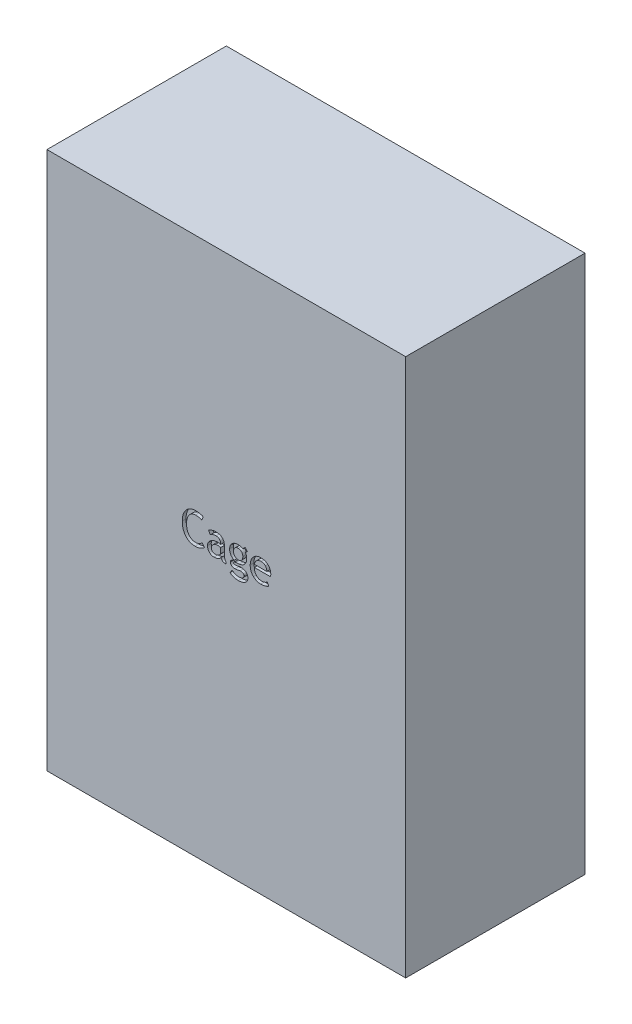
SolidWorks part; units mm, degrees
ref_plane "Front Plane" through (0, 0, 0) normal (0, 0, 1) x (1, 0, 0)
ref_plane "Top Plane" through (0, 0, 0) normal (0, 1, 0) x (1, 0, 0)
ref_plane "Right Plane" through (0, 0, 0) normal (1, 0, 0) x (0, 0, -1)
sketch "Sketch1" plane through (0, 0, 0) normal (0, 1, 0) x (1, 0, 0)
  line L1 (-609.6, -304.8) -> (609.6, -304.8)
  line L2 (-609.6, -304.8) -> (-609.6, 304.8)
  line L3 (-609.6, 304.8) -> (609.6, 304.8)
  line L4 (609.6, -304.8) -> (609.6, 304.8)
  line L5 (-609.6, -304.8) -> (609.6, 304.8) construction
  line L6 (-609.6, 304.8) -> (609.6, -304.8) construction
  point P0 (0, 0)
  dimension "D1" = 609.6
  dimension "D2" = 1219.2
extrude "Boss-Extrude1" add sketch "Sketch1" along normal blind 1828.8
sketch "Sketch2" plane through (0, 0, 304.8) normal (0, 0, 1) x (1, 0, 0)
  line L0 (-609.6, 914.4) -> (609.6, 914.4) construction
  line L1 (-609.6, 1828.8) -> (-609.6, 0) construction
  line L2 (609.6, 1828.8) -> (609.6, 0) construction
  text T0 "Cage" font "Trebuchet MS" height 101.6
extrude "Cut-Extrude1" cut sketch "Sketch2" against normal blind 12.7
